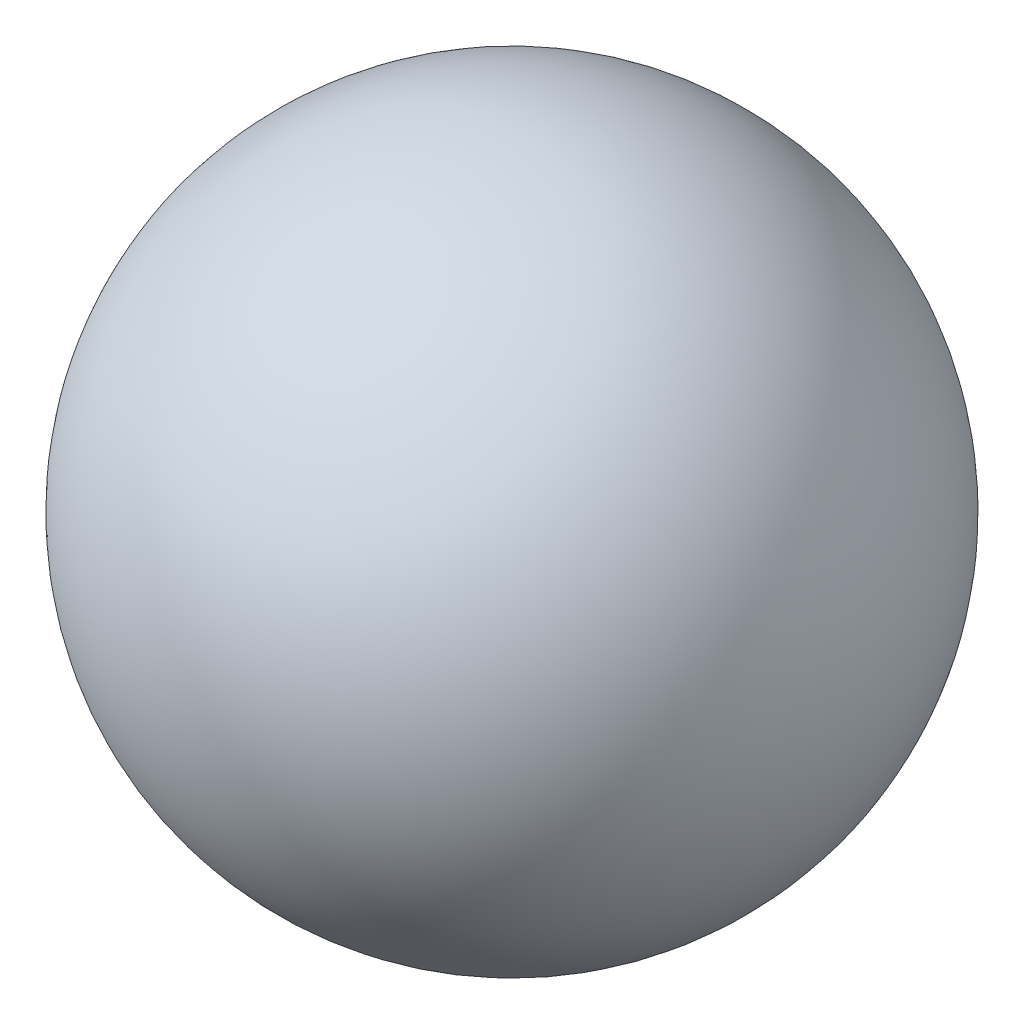
SolidWorks part; units mm, degrees
ref_plane "Front Plane" through (0, 0, 0) normal (0, 0, 1) x (1, 0, 0)
ref_plane "Top Plane" through (0, 0, 0) normal (0, 1, 0) x (1, 0, 0)
ref_plane "Right Plane" through (0, 0, 0) normal (1, 0, 0) x (0, 0, -1)
sketch "Sketch1" plane through (0, 0, 0) normal (0, 0, 1) x (1, 0, 0)
  line L0 (-12, 0) -> (12, 0)
  arc A1 (12, 0) -> (-12, 0) centre (0, 0) cw
  point P4 (0, 0)
  point P6 (0, 0)
  dimension "D1" = 24
revolve "Revolve1" add sketch "Sketch1" angle 360 about L0
